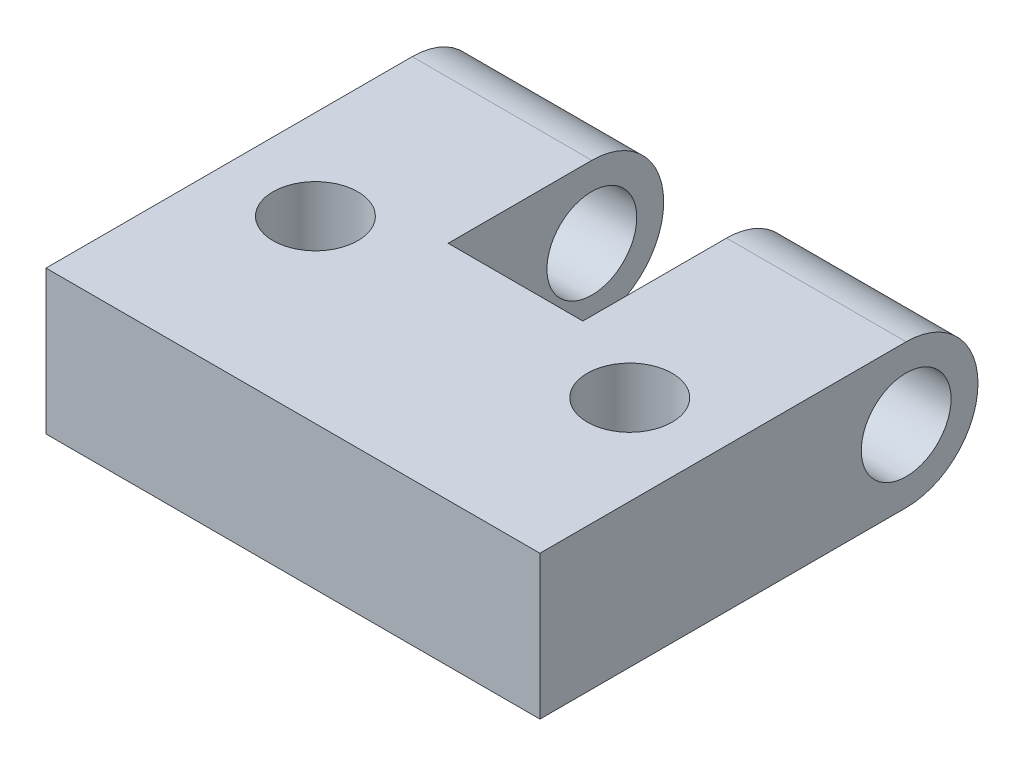
SolidWorks part; units mm, degrees
ref_plane "Front" through (0, 0, 0) normal (0, 0, 1) x (1, 0, 0)
ref_plane "Top" through (0, 0, 0) normal (0, 1, 0) x (1, 0, 0)
ref_plane "Right" through (0, 0, 0) normal (1, 0, 0) x (0, 0, -1)
sketch "Sketch2" plane through (0, 0, 0) normal (1, 0, 0) x (0, 0, -1)
  line L0 (0, 5.08) -> (0, 0)
  line L1 (0, 0) -> (13.1956, 0)
  line L2 (0, 0) -> (0, 5.08)
  line L3 (0, 5.08) -> (13.1956, 5.08)
  line L4 (13.1956, 0) -> (13.1956, 5.08)
  line L5 (0, 5.08) -> (-6.35, 5.08)
  line L6 (0, 0) -> (-6.35, 0)
  line L7 (-6.35, 5.08) -> (-6.35, 0)
  circle A0 centre (6.5978, 2.54) radius 1.5875
  arc A1 (6.5978, 5.08) -> (6.5978, 0) centre (6.5978, 2.54) cw
  point P7 (6.5978, 5.08)
  point P8 (6.5978, 0)
  dimension "D1" = 5.08
  dimension "D2" = 6.35
extrude "Boss-Extrude1" add sketch "Sketch2" along normal blind 6.35 contours L5 L7 L6 L0 | A1 L3 L0 L1 A0
sketch "Sketch3" plane through (0, 5.08, 0) normal (0, 1, 0) x (1, 0, 0)
  line L0 (3.175, -6.35) -> (3.175, 0)
  line L1 (6.35, -6.35) -> (0, -6.35) construction
  circle A0 centre (3.175, 0) radius 1.5
  dimension "D1" = 6.35
extrude "Cut-Extrude1" cut sketch "Sketch3" against normal through all
sketch "Sketch4" plane through (6.35, 0, 0) normal (1, 0, 0) x (0, 0, -1)
  line L0 (6.5978, 2.54) -> (2.6291, 2.54)
  line L1 (6.5978, 2.54) -> (1.5178, 2.54)
  line L2 (6.5978, 0) -> (-6.35, 0) construction
  line L3 (1.5178, 0) -> (-6.35, 0)
  line L4 (1.5178, 0) -> (1.5178, 5.08)
  line L5 (1.5178, 5.08) -> (-6.35, 5.08)
  line L6 (-6.35, 0) -> (-6.35, 5.08)
  line M2 (6.5978, 5.08) -> (-6.35, 5.08)
  line M3 (-6.35, 5.08) -> (-6.35, 0)
  line M4 (-6.35, 0) -> (6.5978, 0)
  dimension "D1" = 3.9688
  dimension "D2" = 5.08
extrude "Boss-Extrude2" add sketch "Sketch4" along normal blind 4.7625 contours L4 M4 M2 M3
ref_plane "Plane1" through (8.7313, 0, 0) normal (1, 0, 0) x (0, 0, -1)
mirror "Mirror1" about plane through (8.7313, 0, 0) normal (1, 0, 0) of "Cut-Extrude1", "Boss-Extrude1"
